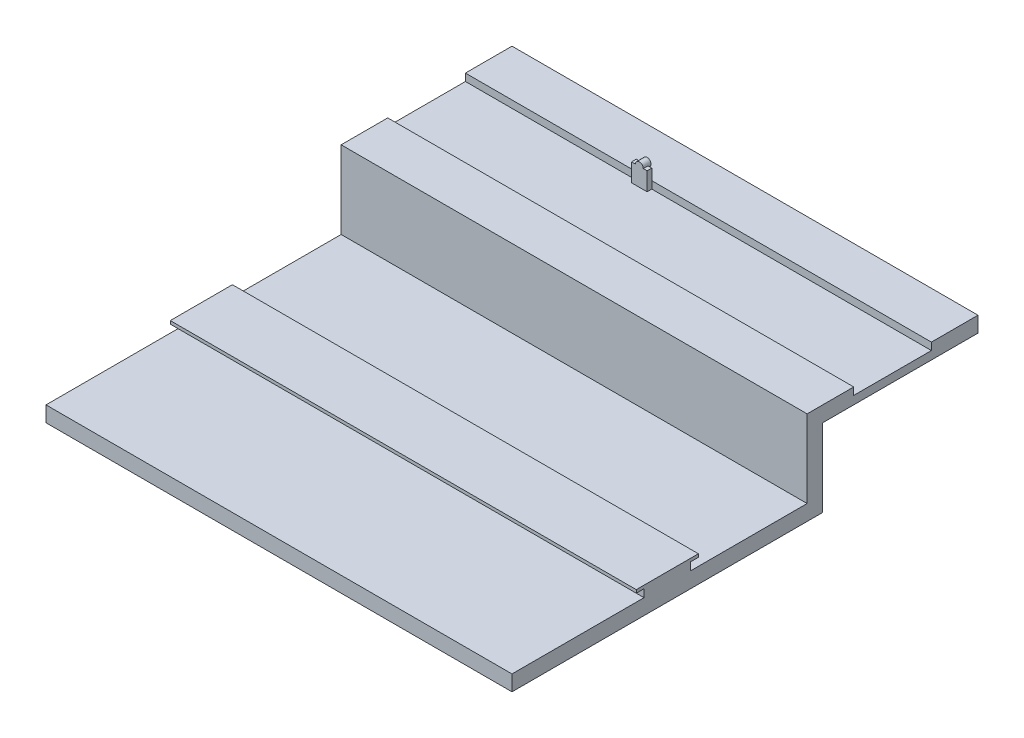
SolidWorks part; units mm, degrees
material "Cast Stainless Steel"
ref_plane "Front Plane" through (0, 0, 0) normal (0, 0, 1) x (1, 0, 0)
ref_plane "Top Plane" through (0, 0, 0) normal (0, 1, 0) x (1, 0, 0)
ref_plane "Right Plane" through (0, 0, 0) normal (1, 0, 0) x (0, 0, -1)
other "Configuration Table"
sketch "Sketch1" plane through (0, 0, 0) normal (1, 0, 0) x (0, 0, -1)
  line L0 (15, 5) -> (100, 5)
  line L1 (-100, 5) -> (-15, 5)
  line L2 (-100, 5) -> (-100, -5)
  line L3 (-100, -5) -> (100, -5)
  line L4 (100, 5) -> (100, -5)
  line L6 (-15, 10) -> (-15, 5)
  line L7 (15, 10) -> (20, 10)
  line L8 (15, 10) -> (15, 5)
  line L9 (-20, 12) -> (20, 12)
  line L10 (-20, 12) -> (-20, 10)
  line L11 (-20, 10) -> (-15, 10)
  line L12 (20, 12) -> (20, 10)
  dimension "D1" = 200
  dimension "D2" = 10
  dimension "D3" = 100
  dimension "D4" = 5
  dimension "D5" = 30
  dimension "D6" = 5
  dimension "D7" = 15
  dimension "D8" = 40
  dimension "D9" = 2
  dimension "D10" = 20
extrude "Extrude1" add sketch "Sketch1" along normal mid plane 300
sketch "Sketch2" plane through (150, 0, 0) normal (1, 0, 0) x (0, 0, -1)
  line L0 (0, 12) -> (0, -5)
  line L1 (20, 12) -> (-20, 12) construction
  line L2 (-100, -5) -> (100, -5) construction
split line "Split Line1" [suppressed]
sketch "Sketch3" plane through (0, 5, 0) normal (0, 1, 0) x (1, 0, 0)
  line L0 (150, 100) -> (150, 15) construction
  line L1 (-150, 100) -> (150, 100)
  line L2 (-150, 100) -> (-150, 90)
  line L3 (-150, 90) -> (150, 90)
  line L4 (150, 100) -> (150, 90)
  dimension "D1" = 10
extrude "Extrude2" add sketch "Sketch3" along normal blind 50
sketch "Sketch4" plane through (0, 0, -100) normal (0, 0, -1) x (-1, 0, 0)
  line L0 (150, -5) -> (150, 55) construction
  line L1 (-150, 55) -> (150, 55)
  line L2 (-150, 55) -> (-150, 45)
  line L3 (-150, 45) -> (150, 45)
  line L4 (150, 55) -> (150, 45)
  dimension "D1" = 10
extrude "Extrude3" add sketch "Sketch4" along normal blind 100
sketch "Sketch5" plane through (150, 0, 0) normal (1, 0, 0) x (0, 0, -1)
  line L0 (90, 55) -> (90, 5) construction
  line L1 (120, 67.2828) -> (170, 67.2828)
  line L2 (120, 67.2828) -> (120, 50.2868)
  line L3 (120, 50.2868) -> (170, 50.2868)
  line L4 (170, 67.2828) -> (170, 50.2868)
  dimension "D1" = 50
  dimension "D2" = 30
extrude "Extrude4" cut sketch "Sketch5" against normal through all
sketch "Sketch6" plane through (0, 0, -170) normal (0, 0, -1) x (-1, 0, 0)
  line L0 (-150, 55) -> (-150, 45) construction
  line L1 (30, 62) -> (32.5, 62)
  line L2 (30, 62) -> (30, 45)
  line L3 (30, 45) -> (40, 45)
  line L4 (40, 62) -> (40, 45)
  line L5 (-150, 45) -> (150, 45) construction
  line L6 (37.5, 62) -> (40, 62)
  line L7 (150, 55) -> (-150, 55) construction
  arc A0 (37.5, 62) -> (32.5, 62) centre (35, 62) ccw
  dimension "D4" = 2.5
  dimension "D1" = 185
  dimension "D2" = 10
  dimension "D3" = 17
  dimension "D5" = 5
  dimension "D6" = 7
extrude "Extrude5" add sketch "Sketch6" against normal blind 3
sketch "Sketch7" plane through (0, 0, -167) normal (0, 0, 1) x (1, 0, 0)
  circle A0 centre (-35, 62) radius 2.5
extrude "Extrude6" add sketch "Sketch7" against normal blind 5
